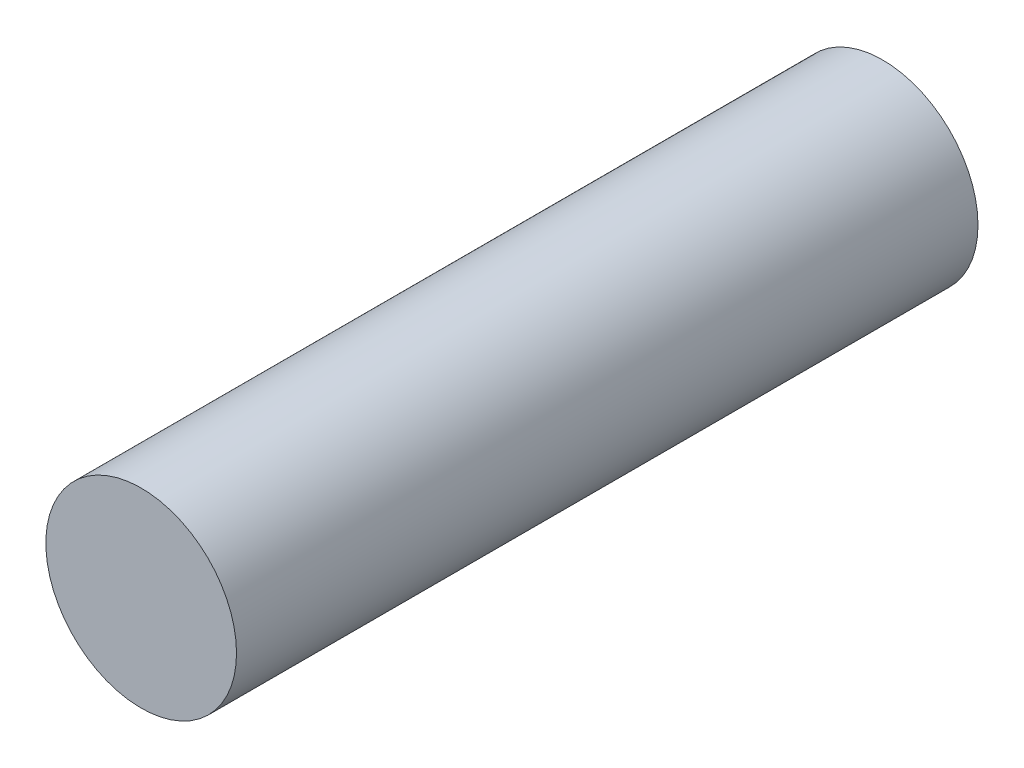
SolidWorks part; units mm, degrees
ref_plane "Спереди" through (0, 0, 0) normal (0, 0, 1) x (1, 0, 0)
ref_plane "Сверху" through (0, 0, 0) normal (0, 1, 0) x (1, 0, 0)
ref_plane "Справа" through (0, 0, 0) normal (1, 0, 0) x (0, 0, -1)
sketch "Эскиз1" plane through (0, 0, 0) normal (0, 0, 1) x (1, 0, 0)
  circle A0 centre (0, 0) radius 9
  dimension "D1" = 18
extrude "Бобышка-Вытянуть1" add sketch "Эскиз1" along normal blind 70
